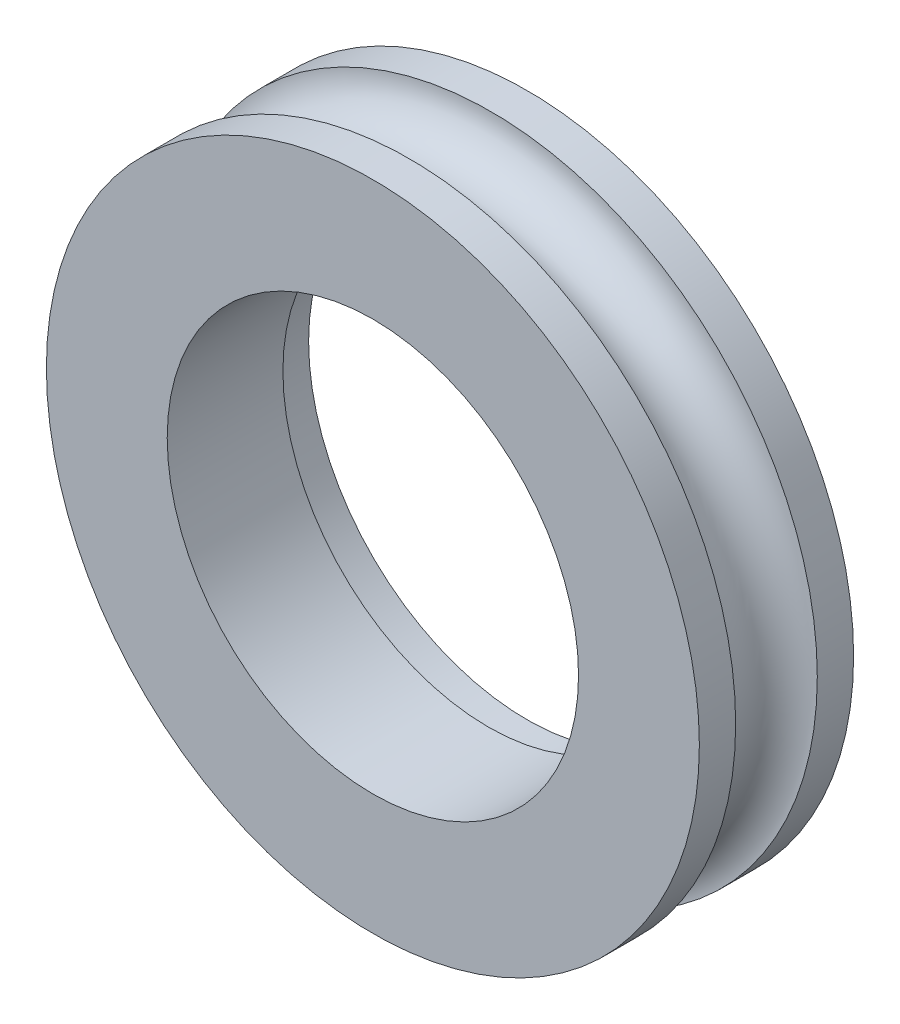
SolidWorks part; units mm, degrees
ref_plane "Front Plane" through (0, 0, 0) normal (0, 0, 1) x (1, 0, 0)
ref_plane "Top Plane" through (0, 0, 0) normal (0, 1, 0) x (1, 0, 0)
ref_plane "Right Plane" through (0, 0, 0) normal (1, 0, 0) x (0, 0, -1)
sketch "Sketch1" plane through (0, 0, 0) normal (0, 1, 0) x (1, 0, 0)
  line L1 (16, 0) -> (25.4, 0)
  line L2 (0, 0) -> (0, 12) construction
  line L3 (16, 12) -> (25.4, 12)
  line L8 (16, 0) -> (16, 12)
  line L9 (25.4, 12) -> (25.4, 9.175)
  line L10 (25.4, 2.825) -> (25.4, 0)
  arc A0 (25.4, 9.175) -> (25.4, 2.825) centre (25.4, 6) ccw
  dimension "D3" = 6.35
  dimension "D4" = 16
  dimension "D1" = 12
  dimension "D2" = 25.4
revolve "Revolve1" add sketch "Sketch1" angle 360 about L2
sketch "Sketch2" plane through (0, 0, -12) normal (0, 0, -1) x (-1, 0, 0)
  circle A0 centre (0, 0) radius 17
  dimension "D1" = 34
extrude "Cut-Extrude1" cut sketch "Sketch2" against normal blind 3
